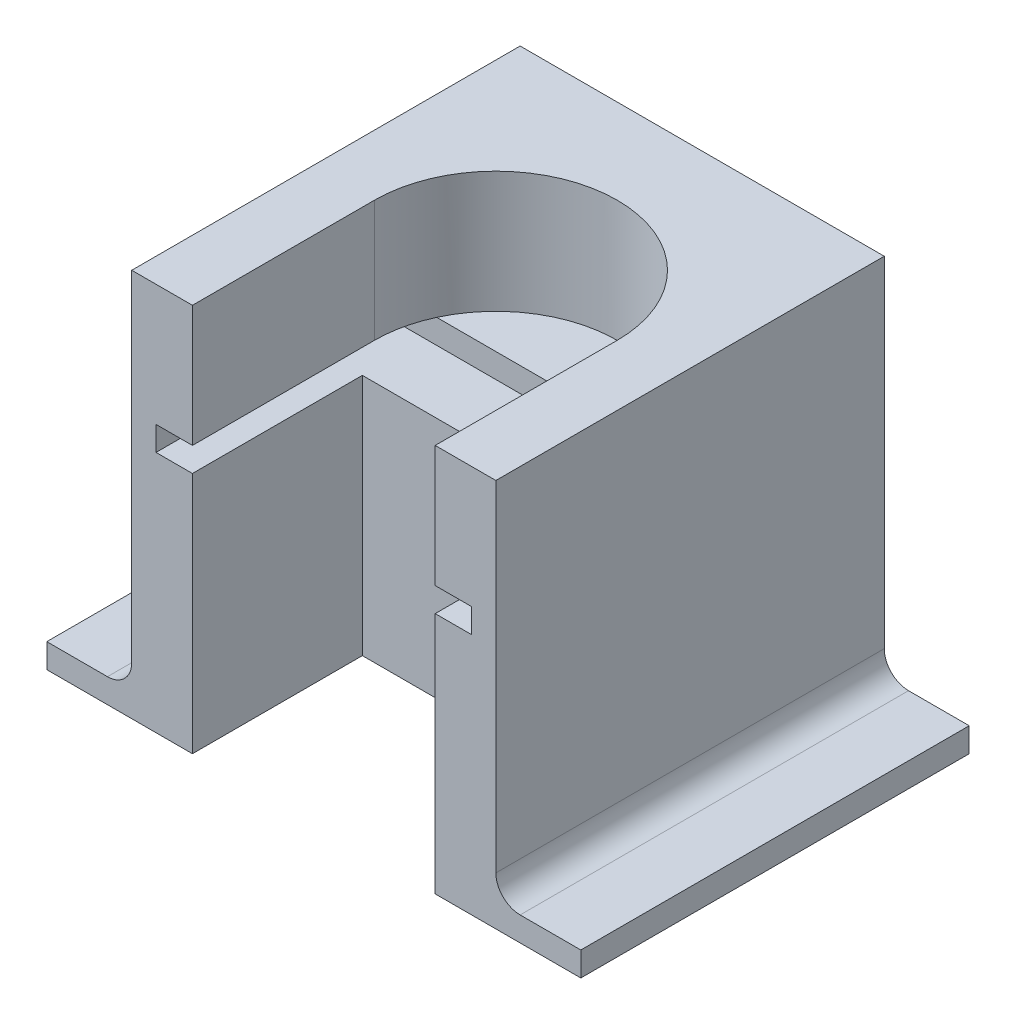
SolidWorks part; units mm, degrees
ref_plane "Front Plane" through (0, 0, 0) normal (0, 0, 1) x (1, 0, 0)
ref_plane "Top Plane" through (0, 0, 0) normal (0, 1, 0) x (1, 0, 0)
ref_plane "Right Plane" through (0, 0, 0) normal (1, 0, 0) x (0, 0, -1)
sketch "Sketch1" plane through (0, 0, 0) normal (0, 1, 0) x (1, 0, 0)
  line L1 (0, 0) -> (-30, 0)
  line L2 (0, 0) -> (0, 28)
  line L3 (0, 28) -> (-30, 28)
  line L4 (-30, 0) -> (-30, 28)
  line L5 (0, 0) -> (-30, 28) construction
  line L6 (0, 28) -> (-30, 0) construction
  point P4 (-15, 14)
  dimension "D1" = 30
  dimension "D2" = 28
extrude "Boss-Extrude1" add sketch "Sketch1" along normal blind 20
sketch "Sketch2" plane through (0, 20, 0) normal (0, 1, 0) x (1, 0, 0)
  line L0 (-15, 28) -> (-15, 0) construction
  line L1 (0, 28) -> (-30, 28) construction
  line L2 (-30, 0) -> (0, 0) construction
  line L3 (-30, 0) -> (-25, 0)
  line L4 (0, 28) -> (-5, 28)
  line L5 (0, 28) -> (0, 0)
  line L6 (0, 0) -> (-5, 0)
  line L7 (-5, 28) -> (-5, 0)
  line L8 (0, 28) -> (-5, 0) construction
  line L9 (0, 0) -> (-5, 28) construction
  line L10 (-25, 28) -> (-25, 0)
  line L11 (-30, 28) -> (-25, 28)
  line L12 (-30, 28) -> (-30, 0)
  point P10 (-2.5, 14)
  dimension "D1" = 20
extrude "Boss-Extrude2" add sketch "Sketch2" along normal blind 12
sketch "Sketch3" plane through (0, 0, 0) normal (0, 0, 1) x (1, 0, 0)
  line L0 (-15, 20) -> (-15, 0) construction
  line L1 (-5, 20) -> (-2, 20)
  line L2 (-5, 20) -> (-5, 22)
  line L3 (-5, 22) -> (-2, 22)
  line L4 (-2, 20) -> (-2, 22)
  line L5 (-5, 20) -> (-2, 22) construction
  line L6 (-5, 22) -> (-2, 20) construction
  line L7 (-25, 20) -> (-5, 20) construction
  line L8 (-30, 0) -> (0, 0) construction
  line L9 (-25, 22) -> (-28, 22)
  line L10 (-28, 20) -> (-28, 22)
  line L11 (-25, 20) -> (-28, 20)
  line L12 (-25, 20) -> (-25, 22)
  point P4 (-3.5, 21)
  dimension "D1" = 3
  dimension "D2" = 2
extrude "Cut-Extrude1" cut sketch "Sketch3" against normal through all
sketch "Sketch4" plane through (0, 0, 0) normal (0, 0, 1) x (1, 0, 0)
  line L0 (-28, 20) -> (-2, 20) construction
  line L1 (-5, 20) -> (-25, 20)
  line L2 (-5, 20) -> (-5, 0)
  line L3 (-5, 0) -> (-25, 0)
  line L4 (-25, 20) -> (-25, 0)
  line L5 (-5, 20) -> (-25, 0) construction
  line L6 (-5, 0) -> (-25, 20) construction
  line L7 (-30, 0) -> (0, 0) construction
  line L8 (-25, 32) -> (-25, 22) construction
  line L9 (-5, 32) -> (-5, 22) construction
  point P4 (-15, 10)
extrude "Cut-Extrude2" cut sketch "Sketch4" against normal blind 14
sketch "Sketch5" plane through (0, 0, -28) normal (0, 0, -1) x (-1, 0, 0)
  line L0 (15, 20) -> (15, 0) construction
  line L1 (30, 0) -> (37, 0)
  line L2 (30, 0) -> (30, 2)
  line L3 (30, 2) -> (37, 2)
  line L4 (37, 0) -> (37, 2)
  line L5 (30, 0) -> (37, 2) construction
  line L6 (30, 2) -> (37, 0) construction
  line L7 (2, 20) -> (28, 20) construction
  line L8 (0, 0) -> (30, 0) construction
  line L9 (0, 2) -> (-7, 2)
  line L10 (-7, 0) -> (-7, 2)
  line L11 (0, 0) -> (-7, 0)
  line L12 (0, 0) -> (0, 2)
  point P4 (33.5, 1)
  dimension "D1" = 2
  dimension "D2" = 7
extrude "Boss-Extrude3" add sketch "Sketch5" against normal up to surface (28 mm away) up to face at (-3, 18.5, 0)
fillet "Fillet1" radius 2 2 edges at (0, 2, -14) (-30, 2, -14)
sketch "Sketch7" plane through (0, 32, 0) normal (0, 1, 0) x (1, 0, 0)
  line L0 (-25, 0) -> (-25, 28) construction
  line L1 (-5, 28) -> (-5, 0) construction
  line L2 (-5, 28) -> (-25, 28) construction
  line L3 (-25, 15) -> (-25, 28)
  line L4 (-25, 28) -> (-5, 28)
  line L5 (-5, 28) -> (-5, 15)
  arc A0 (-5, 15) -> (-25, 15) centre (-15, 15) ccw
  point P10 (-15, 25)
  dimension "D1" = 3
extrude "Boss-Extrude5" add sketch "Sketch7" against normal up to surface (10 mm away) up to face at (-3.5, 22, -14)
sketch "Sketch9" plane through (0, 32, 0) normal (0, 1, 0) x (1, 0, 0)
  arc A0 (-5, 15) -> (-25, 15) centre (-15, 15) ccw construction
  point P0 (-15, 15)
  point P5 (-15, 19.2)
  dimension "D1" = 4.2
sketch "Sketch8" plane through (0, 0, -28) normal (0, 0, -1) x (-1, 0, 0)
  line L0 (2, 20) -> (2, 22) construction
  line L1 (28, 22) -> (28, 20) construction
  line L2 (2, 22) -> (28, 22) construction
  line L3 (2, 20) -> (28, 20) construction
  line L4 (2, 20) -> (2, 22)
  line L5 (28, 22) -> (28, 20)
  line L6 (2, 22) -> (28, 22)
  line L7 (2, 20) -> (28, 20)
extrude "Boss-Extrude6" add sketch "Sketch8" against normal up to vertex (8.8 mm away) up to point (-15, 32, -19.2)
sketch "Sketch10" plane through (0, 0, -28) normal (0, 0, -1) x (-1, 0, 0)
  line L8 (30, 4) -> (30, 32)
  line L9 (30, 32) -> (0, 32)
  line L10 (0, 32) -> (0, 4)
  line L11 (-2, 2) -> (-7, 2)
  line L12 (-7, 2) -> (-7, 0)
  line L13 (-7, 0) -> (37, 0)
  line L14 (37, 0) -> (37, 2)
  line L15 (37, 2) -> (32, 2)
  line L16 (30, 4) -> (30, 32)
  line L17 (30, 32) -> (0, 32)
  line L18 (0, 32) -> (0, 4)
  line L19 (-2, 2) -> (-7, 2)
  line L20 (-7, 2) -> (-7, 0)
  line L21 (-7, 0) -> (37, 0)
  line L22 (37, 0) -> (37, 2)
  line L23 (37, 2) -> (32, 2)
  arc A2 (-2, 2) -> (0, 4) centre (-2, 4) ccw
  arc A3 (30, 4) -> (32, 2) centre (32, 4) ccw
  arc A4 (-2, 2) -> (0, 4) centre (-2, 4) ccw
  arc A5 (30, 4) -> (32, 2) centre (32, 4) ccw
  dimension "D1" = 0
extrude "Boss-Extrude7" add sketch "Sketch10" along normal blind 4
